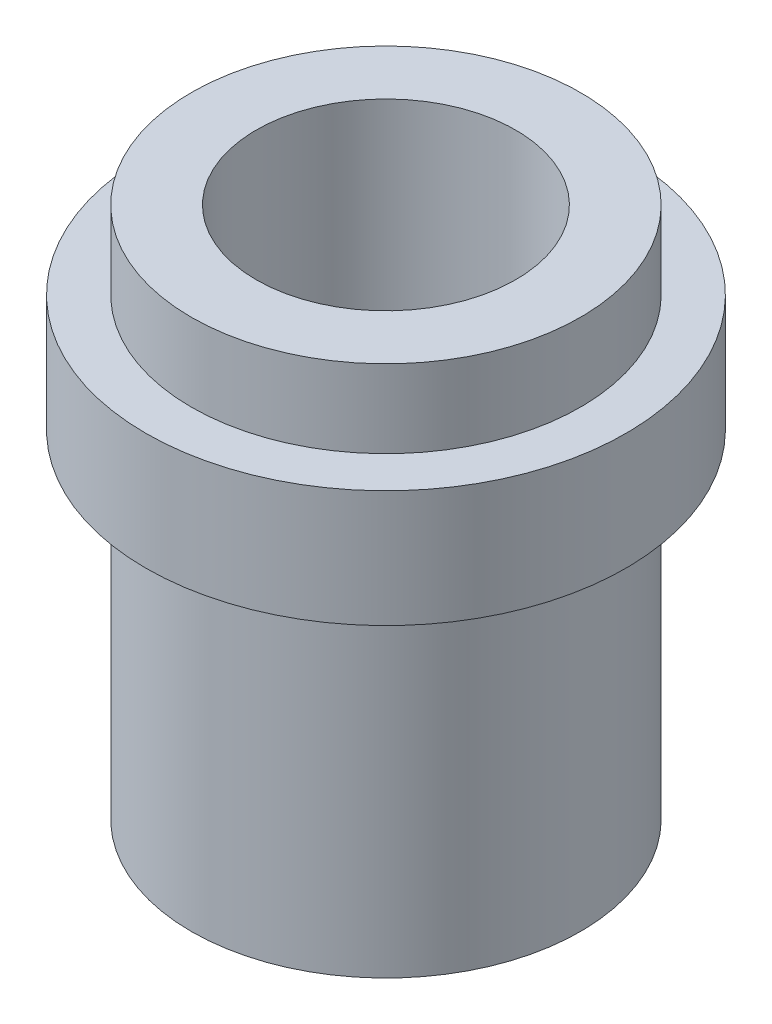
SolidWorks part; units mm, degrees
ref_plane "Спереди" through (0, 0, 0) normal (0, 0, 1) x (1, 0, 0)
ref_plane "Сверху" through (0, 0, 0) normal (0, 1, 0) x (1, 0, 0)
ref_plane "Справа" through (0, 0, 0) normal (1, 0, 0) x (0, 0, -1)
sketch "Эскиз1" plane through (0, 0, 0) normal (0, 0, 1) x (1, 0, 0)
  line L0 (0, 46.5034) -> (0, -53.198) construction
  line L1 (0, 33.5814) -> (15, 33.5814)
  line L2 (15, 33.5814) -> (15, 27.5814)
  line L3 (15, 27.5814) -> (18.5, 27.5814)
  line L4 (18.5, 27.5814) -> (18.5, 18.5814)
  line L5 (18.5, 18.5814) -> (15, 18.5814)
  line L6 (15, 18.5814) -> (15, -7.4186)
  line L7 (15, -7.4186) -> (0, -7.4186)
  line L8 (0, 33.5814) -> (0, -7.4186)
  dimension "D1" = 15
  dimension "D2" = 15
  dimension "D3" = 18.5
  dimension "D4" = 6
  dimension "D5" = 9
  dimension "D6" = 26
revolve "Повернуть1" add sketch "Эскиз1" angle 360 about L0
sketch "Эскиз2" plane through (0, 33.5814, 0) normal (0, 1, 0) x (1, 0, 0)
  circle A0 centre (0, 0) radius 10
  dimension "D1" = 20
extrude "Вырез-Вытянуть1" cut sketch "Эскиз2" against normal blind 45
